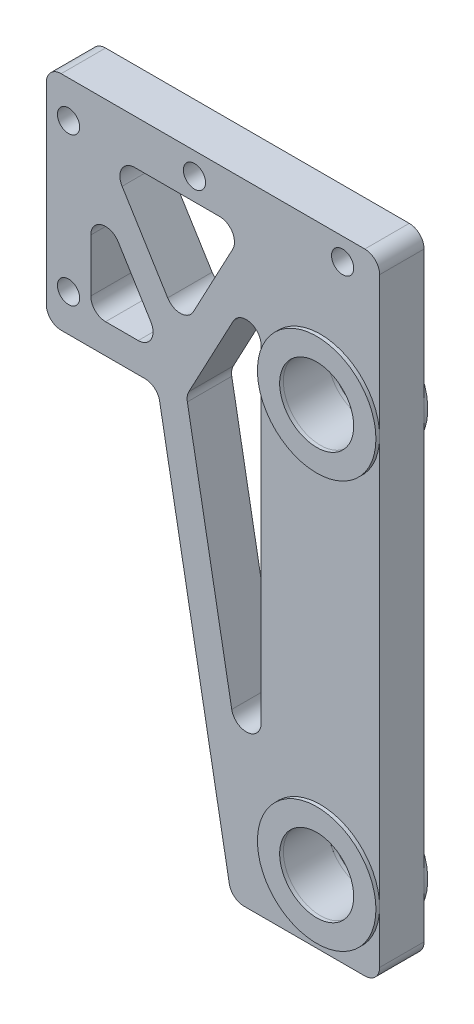
SolidWorks part; units mm, degrees
material "Thornel Mat VMA"
ref_plane "前视基准面" through (0, 0, 0) normal (0, 0, 1) x (1, 0, 0)
ref_plane "上视基准面" through (0, 0, 0) normal (0, 1, 0) x (1, 0, 0)
ref_plane "右视基准面" through (0, 0, 0) normal (1, 0, 0) x (0, 0, -1)
other "Configuration Table"
sketch "草图1" plane through (0, 0, 0) normal (0, 0, 1) x (1, 0, 0)
  line L0 (0, 0) -> (0, -55) construction
  line L1 (-37, 20.95) -> (8, 20.95)
  line L2 (8, 20.95) -> (8, -64.05)
  line L3 (8, -64.05) -> (-12, -64.05)
  line L4 (-12, -64.05) -> (-22, -9.05)
  line L5 (-22, -9.05) -> (-37, -9.05)
  line L6 (-37, -9.05) -> (-37, 20.95)
  line L7 (-17, 17.95) -> (3, 17.95) construction
  line L8 (-34, 15.95) -> (-34, -4.05) construction
  circle A0 centre (0, 0) radius 6
  circle A1 centre (0, -55) radius 6
  circle A2 centre (3, 17.95) radius 1.5
  circle A3 centre (-17, 17.95) radius 1.5
  circle A4 centre (-34, 15.95) radius 1.5
  circle A5 centre (-34, -4.05) radius 1.5
  dimension "D1" = 12
  dimension "D4" = 20.95
  dimension "D10" = 3
  dimension "D12" = 5
  dimension "D13" = 5
  dimension "D2" = 55
  dimension "D3" = 8
  dimension "D5" = 45
  dimension "D6" = 20
  dimension "D7" = 15
  dimension "D8" = 85
  dimension "D9" = 30
  dimension "D11" = 20
  dimension "D14" = 3
  dimension "D15" = 3
extrude "凸台-拉伸1" add sketch "草图1" along normal blind 6
sketch "草图2" plane through (0, 0, 6) normal (0, 0, 1) x (1, 0, 0)
  circle A0 centre (0, 0) radius 5
  circle A1 centre (0, -55) radius 5
  circle A2 centre (0, -55) radius 6 construction
  circle A3 centre (0, 0) radius 6 construction
  circle A4 centre (0, -55) radius 6
  circle A5 centre (0, 0) radius 6
  dimension "D1" = 10
extrude "凸台-拉伸2" add sketch "草图2" against normal blind 6 separate body
sketch "草图3" plane through (0, 0, 6) normal (0, 0, 1) x (1, 0, 0)
  line L0 (-8, 14.95) -> (-8, -63.6893)
  line L1 (-8, -63.6893) -> (-18.6617, -5.05)
  line L2 (-18.6617, -5.05) -> (-31, -5.05)
  line L3 (-31, -5.05) -> (-31, 14.95)
  line L4 (-31, 14.95) -> (-8, 14.95)
  line L5 (8, 20.95) -> (-37, 20.95) construction
  line L6 (-37, 20.95) -> (-37, -9.05) construction
  line L7 (-37, -9.05) -> (-22, -9.05) construction
  line L8 (-22, -9.05) -> (-12, -64.05) construction
  line L9 (-18.6617, -5.05) -> (-8, 14.95) construction
  line L10 (-18.6617, -5.05) -> (-31, 14.95) construction
  line L11 (-31, 11.1408) -> (-21.0117, -5.05)
  line L12 (-28.65, 14.95) -> (-18.7882, -1.0357)
  line L13 (-18.7882, -1.0357) -> (-10.2664, 14.95)
  line L14 (-8, 10.6985) -> (-18.0853, -8.2203)
  circle A0 centre (0, 0) radius 6 construction
  dimension "D1" = 6
  dimension "D2" = 6
  dimension "D3" = 4
  dimension "D4" = 4
  dimension "D5" = 8
  dimension "D6" = 2
  dimension "D7" = 2
  dimension "D8" = 2
  dimension "D9" = 2
extrude "切除-拉伸1" cut sketch "草图3" against normal up to surface (6 mm away) contours L0 L14 L1 | L12 L13 L4 | L11 L3 L2 up to face at (-32.5, 15.95, 0)
fillet "圆角2" radius 2 15 edges at (-31, 11.1408, 3) (-31, -5.05, 3) (-21.0117, -5.05, 3) (-8, -63.6893, 3) (-8, 10.6985, 3) (-18.0853, -8.2203, 3) (8, -64.05, 3) (-22, -9.05, 3) (-37, -9.05, 3) (-37, 20.95, 3) (8, 20.95, 3) (-28.65, 14.95, 3) (-18.7882, -1.0357, 3) (-10.2664, 14.95, 3) (-12, -64.05, 3)
sketch "草图4" plane through (0, 0, 6) normal (0, 0, 1) x (1, 0, 0)
  circle A0 centre (0, 0) radius 8
  circle A1 centre (0, 0) radius 5
  circle A2 centre (0, -55) radius 5
  circle A3 centre (0, -55) radius 8
  dimension "D1" = 10
  dimension "D2" = 16
extrude "凸台-拉伸3" add sketch "草图4" along normal blind 0.5 separate body
sketch "草图5" plane through (0, 0, 0) normal (0, 0, -1) x (-1, 0, 0)
  circle A0 centre (0, -55) radius 8 construction
  circle A1 centre (0, 0) radius 8 construction
  circle A2 centre (0, -55) radius 8
  circle A3 centre (0, 0) radius 8
  circle A4 centre (0, -55) radius 5 construction
  circle A5 centre (0, 0) radius 5 construction
  circle A6 centre (0, -55) radius 5
  circle A7 centre (0, 0) radius 5
extrude "凸台-拉伸4" add sketch "草图5" along normal blind 0.5 separate body
